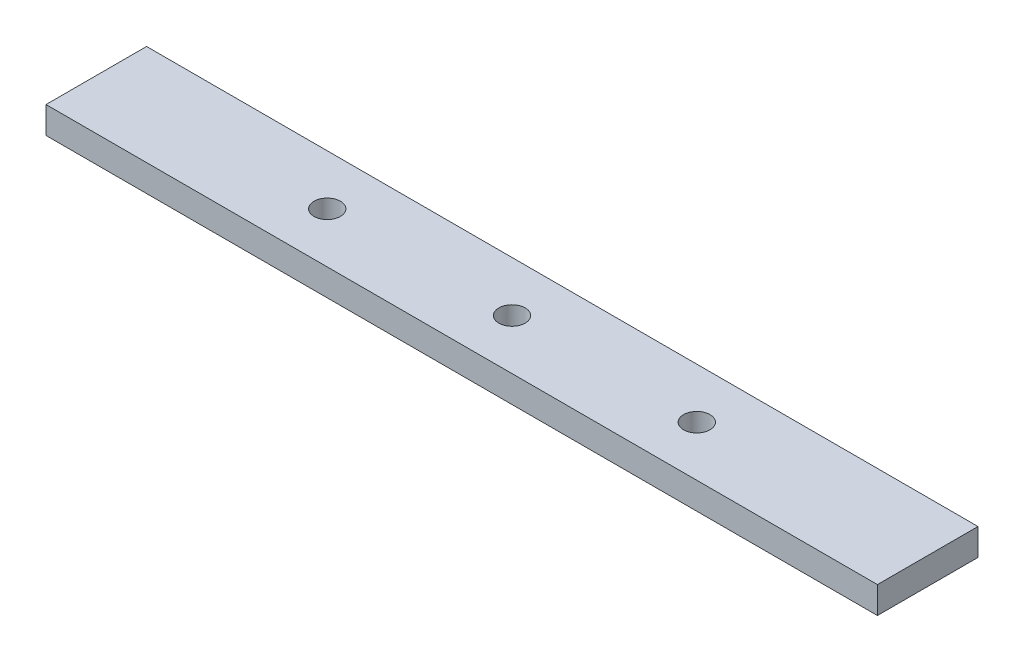
SolidWorks part; units mm, degrees
ref_plane "Front Plane" through (0, 0, 0) normal (0, 0, 1) x (1, 0, 0)
ref_plane "Top Plane" through (0, 0, 0) normal (0, 1, 0) x (1, 0, 0)
ref_plane "Right Plane" through (0, 0, 0) normal (1, 0, 0) x (0, 0, -1)
sketch "Sketch1" plane through (0, 0, 0) normal (0, 1, 0) x (1, 0, 0)
  line L1 (0, 0) -> (314.96, 0)
  line L2 (0, 0) -> (0, -38.1)
  line L3 (0, -38.1) -> (314.96, -38.1)
  line L4 (314.96, 0) -> (314.96, -38.1)
  dimension "D1" = 38.1
  dimension "D2" = 314.96
extrude "Boss-Extrude1" add sketch "Sketch1" along normal blind 10.16
sketch "Sketch2" plane through (0, 10.16, 0) normal (0, 1, 0) x (1, 0, 0)
  line L2 (0, 0) -> (0, -38.1) construction
  line L6 (87.48, -19.05) -> (87.48, 0)
  line L7 (314.96, 0) -> (0, 0) construction
  line L8 (87.48, -19.05) -> (87.48, -38.1)
  line L9 (0, -38.1) -> (314.96, -38.1) construction
  circle A0 centre (87.48, -19.05) radius 5
  circle A1 centre (157.48, -19.05) radius 5
  circle A2 centre (227.48, -19.05) radius 5
  dimension "D1" = 10
  dimension "D2" = 10
  dimension "D3" = 10
  dimension "D4" = 157.48
  dimension "D5" = 70
  dimension "D6" = 70
extrude "Cut-Extrude1" cut sketch "Sketch2" against normal blind 47.16 contours A0 | A1 | A2
